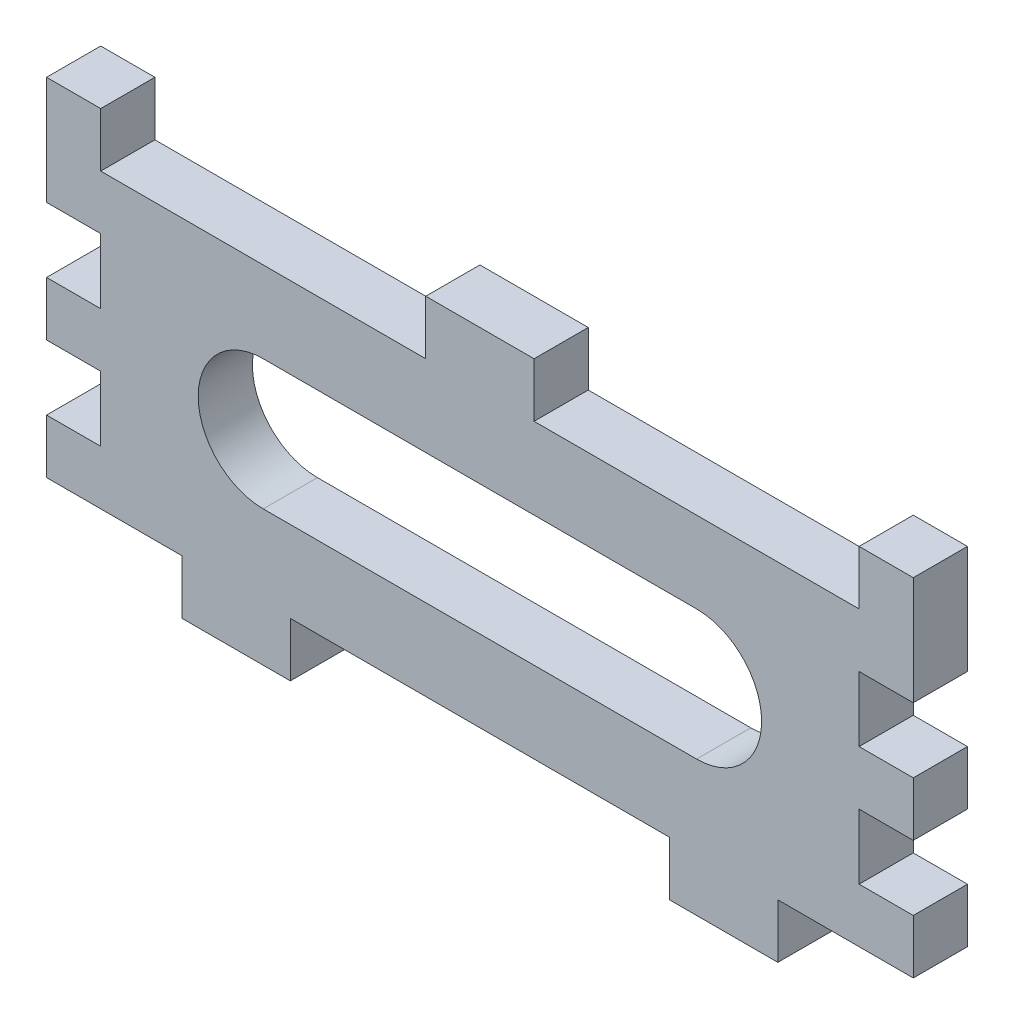
SolidWorks part; units mm, degrees
material "Balsa"
ref_plane "Plan de face" through (0, 0, 0) normal (0, 0, 1) x (1, 0, 0)
ref_plane "Plan de dessus" through (0, 0, 0) normal (0, 1, 0) x (1, 0, 0)
ref_plane "Plan de droite" through (0, 0, 0) normal (1, 0, 0) x (0, 0, -1)
sketch "Esquisse1" plane through (0, 0, 0) normal (0, 0, 1) x (1, 0, 0)
  line L1 (58.9836, 170.4211) -> (138.9836, 170.4211)
  line L2 (58.9836, 170.4211) -> (58.9836, 143.4211)
  line L3 (58.9836, 143.4211) -> (138.9836, 143.4211)
  line L4 (138.9836, 170.4211) -> (138.9836, 143.4211)
extrude "Boss.-Extru.1" add sketch "Esquisse1" against normal blind 5
sketch "Esquisse3" plane through (0, 0, 0) normal (0, 0, 1) x (1, 0, 0)
  line L0 (58.9836, 170.4211) -> (58.9836, 143.4211) construction
  line L1 (58.9836, 165.4211) -> (63.9836, 165.4211)
  line L2 (58.9836, 165.4211) -> (58.9836, 159.4211)
  line L3 (58.9836, 159.4211) -> (63.9836, 159.4211)
  line L4 (63.9836, 165.4211) -> (63.9836, 159.4211)
  line L5 (98.9836, 223.4211) -> (98.9836, 138.4211) construction
  line L6 (63.9836, 154.4211) -> (58.9836, 154.4211)
  line L7 (63.9836, 154.4211) -> (63.9836, 148.4211)
  line L8 (63.9836, 148.4211) -> (58.9836, 148.4211)
  line L9 (58.9836, 154.4211) -> (58.9836, 148.4211)
  line L10 (138.9836, 154.4211) -> (138.9836, 148.4211)
  line L11 (133.9836, 148.4211) -> (138.9836, 148.4211)
  line L12 (133.9836, 154.4211) -> (133.9836, 148.4211)
  line L13 (133.9836, 154.4211) -> (138.9836, 154.4211)
  line L14 (133.9836, 165.4211) -> (133.9836, 159.4211)
  line L15 (138.9836, 159.4211) -> (133.9836, 159.4211)
  line L16 (138.9836, 165.4211) -> (138.9836, 159.4211)
  line L17 (138.9836, 165.4211) -> (133.9836, 165.4211)
  line L18 (138.9836, 170.4211) -> (58.9836, 170.4211) construction
  line L19 (58.9836, 143.4211) -> (138.9836, 143.4211) construction
  line L20 (78.9836, 156.9211) -> (118.9836, 156.9211) construction
  line L21 (78.9836, 162.9211) -> (118.9836, 162.9211)
  line L22 (78.9836, 150.9211) -> (118.9836, 150.9211)
  arc A0 (78.9836, 162.9211) -> (78.9836, 150.9211) centre (78.9836, 156.9211) ccw
  arc A1 (118.9836, 150.9211) -> (118.9836, 162.9211) centre (118.9836, 156.9211) ccw
  point P26 (98.9836, 156.9211)
  dimension "D1" = 5
  dimension "D2" = 5
  dimension "D3" = 6
  dimension "D4" = 6
  dimension "D5" = 5
  dimension "D6" = 40
  dimension "D7" = 12
  dimension "D8" = 13.5
extrude "Créneaux -" cut sketch "Esquisse3" against normal blind 5
sketch "Esquisse2" plane through (0, 0, 0) normal (0, 0, 1) x (1, 0, 0)
  line L0 (98.9836, 205.3702) -> (98.9836, 138.4211) construction
  line L1 (133.9836, 175.4211) -> (138.9836, 175.4211)
  line L2 (133.9836, 175.4211) -> (133.9836, 170.4211)
  line L3 (133.9836, 170.4211) -> (138.9836, 170.4211)
  line L4 (138.9836, 175.4211) -> (138.9836, 170.4211)
  line L5 (58.9836, 175.4211) -> (58.9836, 170.4211)
  line L6 (63.9836, 170.4211) -> (58.9836, 170.4211)
  line L7 (63.9836, 175.4211) -> (63.9836, 170.4211)
  line L8 (63.9836, 175.4211) -> (58.9836, 175.4211)
  line L9 (53.9836, 143.4211) -> (143.9836, 143.4211) construction
  line L10 (93.9836, 175.4211) -> (93.9836, 170.4211)
  line L11 (138.9836, 170.4211) -> (58.9836, 170.4211) construction
  line L12 (103.9836, 175.4211) -> (103.9836, 170.4211)
  line L13 (93.9836, 170.4211) -> (103.9836, 170.4211)
  line L14 (103.9836, 175.4211) -> (93.9836, 175.4211)
  line L15 (116.4836, 143.4211) -> (116.4836, 138.4211)
  line L16 (71.4836, 143.4211) -> (81.4836, 143.4211)
  line L17 (71.4836, 143.4211) -> (71.4836, 138.4211)
  line L18 (71.4836, 138.4211) -> (81.4836, 138.4211)
  line L19 (81.4836, 143.4211) -> (81.4836, 138.4211)
  line L20 (126.4836, 138.4211) -> (116.4836, 138.4211)
  line L21 (126.4836, 143.4211) -> (126.4836, 138.4211)
  line L22 (126.4836, 143.4211) -> (116.4836, 143.4211)
  dimension "D1" = 5
  dimension "D2" = 5
  dimension "D3" = 40
  dimension "D4" = 32
  dimension "D5" = 5
  dimension "D6" = 10
  dimension "D7" = 5
  dimension "D8" = 10
  dimension "D9" = 35
extrude "Créneaux +" add sketch "Esquisse2" against normal blind 5
